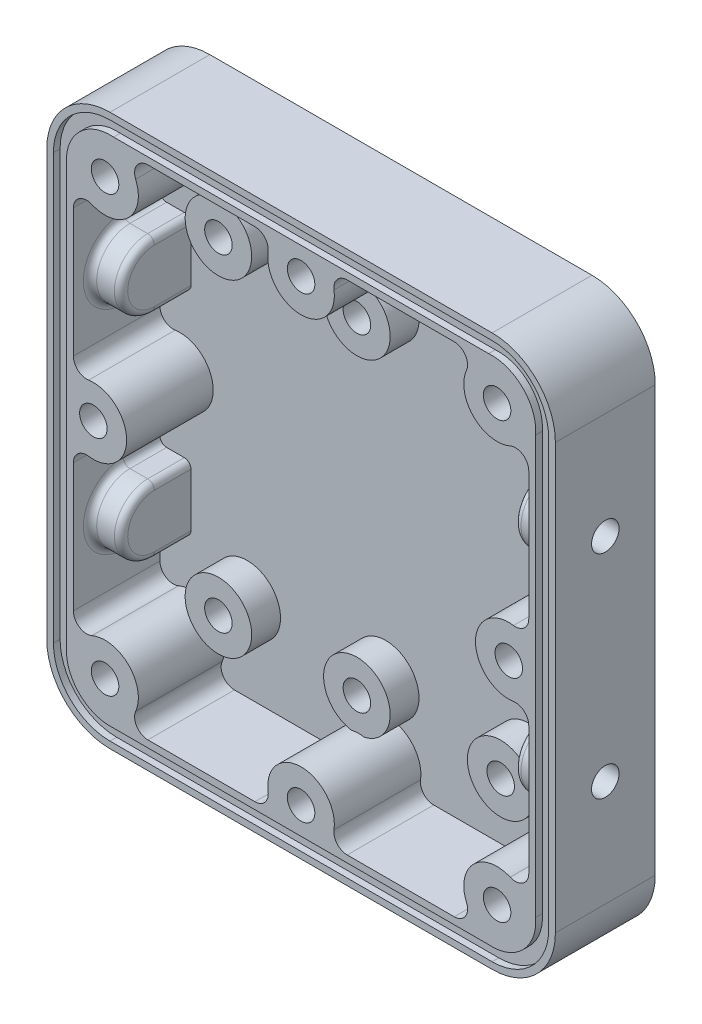
SolidWorks part; units mm, degrees
material "ABS"
ref_plane "X-Y Datum" through (0, 0, 0) normal (0, 0, 1) x (1, 0, 0)
ref_plane "X-Z Datum" through (0, 0, 0) normal (0, 1, 0) x (1, 0, 0)
ref_plane "Y-Z Datum" through (0, 0, 0) normal (1, 0, 0) x (0, 0, -1)
sketch "Sketch2" plane through (0, 0, 0) normal (0, 0, 1) x (1, 0, 0)
  line L5 (20.066, 67.818) -> (84.074, 67.818) construction
  line L6 (20.066, 67.818) -> (20.066, 139.954) construction
  line L7 (20.066, 139.954) -> (84.074, 139.954) construction
  line L8 (84.074, 67.818) -> (84.074, 139.954) construction
  line L9 (20.066, 67.818) -> (84.074, 139.954) construction
  line L10 (20.066, 139.954) -> (84.074, 67.818) construction
  line L14 (6.096, 153.924) -> (98.044, 153.924) construction
  line L15 (98.044, 53.848) -> (98.044, 153.924) construction
  line L16 (6.096, 53.848) -> (98.044, 53.848) construction
  line L17 (6.096, 53.848) -> (6.096, 153.924) construction
  line L18 (15.621, 153.924) -> (88.519, 153.924)
  line L19 (98.044, 63.373) -> (98.044, 144.399)
  line L20 (15.621, 53.848) -> (88.519, 53.848)
  line L21 (6.096, 63.373) -> (6.096, 144.399)
  line L22 (20.066, 103.886) -> (12.446, 103.886) construction
  line L23 (52.07, 67.818) -> (52.07, 60.198) construction
  line L24 (84.074, 103.886) -> (91.694, 103.886) construction
  line L25 (52.07, 139.954) -> (52.07, 147.574) construction
  line L26 (20.066, 139.954) -> (14.6778, 145.3421) construction
  circle A0 centre (25.292, 135.128) radius 2.1 construction
  circle A1 centre (51.708, 135.128) radius 2.1 construction
  circle A2 centre (79.14, 135.128) radius 2.1 construction
  circle A3 centre (51.708, 72.644) radius 2.1 construction
  circle A4 centre (79.14, 72.644) radius 2.1 construction
  circle A5 centre (25.292, 72.644) radius 2.1 construction
  arc A10 (88.519, 153.924) -> (98.044, 144.399) centre (88.519, 144.399) cw
  arc A11 (98.044, 63.373) -> (88.519, 53.848) centre (88.519, 63.373) cw
  arc A12 (15.621, 53.848) -> (6.096, 63.373) centre (15.621, 63.373) cw
  arc A13 (15.621, 153.924) -> (6.096, 144.399) centre (15.621, 144.399) ccw
  circle A20 centre (12.446, 103.886) radius 6.35 construction
  circle A21 centre (52.07, 60.198) radius 6.35 construction
  circle A22 centre (91.694, 103.886) radius 6.35 construction
  circle A23 centre (52.07, 147.574) radius 6.35 construction
  circle A24 centre (14.6778, 145.3421) radius 6.35 construction
  circle A25 centre (89.4622, 145.3421) radius 6.35 construction
  circle A26 centre (89.4622, 62.4298) radius 6.35 construction
  circle A27 centre (14.6778, 62.4298) radius 6.35 construction
  point P18 (52.07, 103.886)
  point P32 (20.066, 139.954)
  dimension "D1" = 9.525
  dimension "D3" = 13.97
extrude "Boss-Extrude1" add sketch "Sketch2" along normal blind 16.51
shell "Shell1" thickness 2.54
sketch "Sketch4" plane through (0, 0, 16.51) normal (0, 0, 1) x (1, 0, 0)
  line L8 (88.519, 155.194) -> (15.621, 155.194)
  line L9 (99.314, 63.373) -> (99.314, 144.399)
  line L10 (15.621, 52.578) -> (88.519, 52.578)
  line L11 (4.826, 144.399) -> (4.826, 63.373)
  line L12 (88.519, 155.194) -> (15.621, 155.194)
  line L13 (99.314, 63.373) -> (99.314, 144.399)
  line L14 (15.621, 52.578) -> (88.519, 52.578)
  line L15 (4.826, 144.399) -> (4.826, 63.373)
  line L20 (88.519, 153.924) -> (15.621, 153.924)
  line L21 (98.044, 63.373) -> (98.044, 144.399)
  line L22 (15.621, 53.848) -> (88.519, 53.848)
  line L23 (6.096, 144.399) -> (6.096, 63.373)
  line L24 (88.519, 153.924) -> (15.621, 153.924)
  line L25 (98.044, 63.373) -> (98.044, 144.399)
  line L26 (15.621, 53.848) -> (88.519, 53.848)
  line L27 (6.096, 144.399) -> (6.096, 63.373)
  arc A8 (99.314, 144.399) -> (88.519, 155.194) centre (88.519, 144.399) ccw
  arc A9 (88.519, 52.578) -> (99.314, 63.373) centre (88.519, 63.373) ccw
  arc A10 (4.826, 63.373) -> (15.621, 52.578) centre (15.621, 63.373) ccw
  arc A11 (15.621, 155.194) -> (4.826, 144.399) centre (15.621, 144.399) ccw
  arc A12 (99.314, 144.399) -> (88.519, 155.194) centre (88.519, 144.399) ccw
  arc A13 (88.519, 52.578) -> (99.314, 63.373) centre (88.519, 63.373) ccw
  arc A14 (4.826, 63.373) -> (15.621, 52.578) centre (15.621, 63.373) ccw
  arc A15 (15.621, 155.194) -> (4.826, 144.399) centre (15.621, 144.399) ccw
  arc A20 (98.044, 144.399) -> (88.519, 153.924) centre (88.519, 144.399) ccw
  arc A21 (88.519, 53.848) -> (98.044, 63.373) centre (88.519, 63.373) ccw
  arc A22 (6.096, 63.373) -> (15.621, 53.848) centre (15.621, 63.373) ccw
  arc A23 (15.621, 153.924) -> (6.096, 144.399) centre (15.621, 144.399) ccw
  arc A24 (98.044, 144.399) -> (88.519, 153.924) centre (88.519, 144.399) ccw
  arc A25 (88.519, 53.848) -> (98.044, 63.373) centre (88.519, 63.373) ccw
  arc A26 (6.096, 63.373) -> (15.621, 53.848) centre (15.621, 63.373) ccw
  arc A27 (15.621, 153.924) -> (6.096, 144.399) centre (15.621, 144.399) ccw
  dimension "D1" = 1.27
  dimension "D2" = 0
extrude "Cut-Extrude1" cut sketch "Sketch4" against normal blind 1.27
sketch "Sketch5" plane through (0, 0, 0) normal (0, 0, 1) x (1, 0, 0)
  line L20 (7.3152, 144.399) -> (7.3152, 63.373)
  line L21 (15.621, 55.0672) -> (88.519, 55.0672)
  line L22 (96.8248, 63.373) -> (96.8248, 144.399)
  line L23 (88.519, 152.7048) -> (15.621, 152.7048)
  line L24 (7.3152, 144.399) -> (7.3152, 63.373)
  line L25 (15.621, 55.0672) -> (88.519, 55.0672)
  line L26 (96.8248, 63.373) -> (96.8248, 144.399)
  line L27 (88.519, 152.7048) -> (15.621, 152.7048)
  line L48 (98.044, 63.373) -> (98.044, 144.399)
  line L49 (15.621, 53.848) -> (88.519, 53.848)
  line L50 (6.096, 144.399) -> (6.096, 63.373)
  line L51 (88.519, 153.924) -> (15.621, 153.924)
  line L52 (98.044, 63.373) -> (98.044, 144.399)
  line L53 (15.621, 53.848) -> (88.519, 53.848)
  line L54 (6.096, 144.399) -> (6.096, 63.373)
  line L55 (88.519, 153.924) -> (15.621, 153.924)
  arc A32 (7.3152, 63.373) -> (15.621, 55.0672) centre (15.621, 63.373) ccw
  arc A33 (88.519, 55.0672) -> (96.8248, 63.373) centre (88.519, 63.373) ccw
  arc A34 (96.8248, 144.399) -> (88.519, 152.7048) centre (88.519, 144.399) ccw
  arc A35 (15.621, 152.7048) -> (7.3152, 144.399) centre (15.621, 144.399) ccw
  arc A36 (7.3152, 63.373) -> (15.621, 55.0672) centre (15.621, 63.373) ccw
  arc A37 (88.519, 55.0672) -> (96.8248, 63.373) centre (88.519, 63.373) ccw
  arc A38 (96.8248, 144.399) -> (88.519, 152.7048) centre (88.519, 144.399) ccw
  arc A39 (15.621, 152.7048) -> (7.3152, 144.399) centre (15.621, 144.399) ccw
  arc A56 (98.044, 144.399) -> (88.519, 153.924) centre (88.519, 144.399) ccw
  arc A57 (88.519, 53.848) -> (98.044, 63.373) centre (88.519, 63.373) ccw
  arc A58 (6.096, 63.373) -> (15.621, 53.848) centre (15.621, 63.373) ccw
  arc A59 (15.621, 153.924) -> (6.096, 144.399) centre (15.621, 144.399) ccw
  arc A60 (98.044, 144.399) -> (88.519, 153.924) centre (88.519, 144.399) ccw
  arc A61 (88.519, 53.848) -> (98.044, 63.373) centre (88.519, 63.373) ccw
  arc A62 (6.096, 63.373) -> (15.621, 53.848) centre (15.621, 63.373) ccw
  arc A63 (15.621, 153.924) -> (6.096, 144.399) centre (15.621, 144.399) ccw
  dimension "D1" = 2.4892
  dimension "D2" = 0
extrude "Boss-Extrude2" add sketch "Sketch5" along normal up to surface (15.24 mm away) up to face at (52.07, 103.886, 15.24)
sketch "Sketch7" plane through (0, 0, 0) normal (0, 0, 1) x (1, 0, 0)
  line L1 (19.168, 149.8323) -> (16.2955, 152.7048)
  line L3 (10.1877, 140.852) -> (7.3152, 143.7245)
  line L4 (7.3152, 144.399) -> (7.3152, 63.373) construction
  line L5 (88.519, 152.7048) -> (15.621, 152.7048) construction
  line L6 (52.07, 103.886) -> (52.07, 122.8885) construction
  line L7 (1144.018, 103.886) -> (98.044, 103.886) construction
  line L8 (93.9523, 140.852) -> (96.8248, 143.7245)
  line L9 (84.972, 149.8323) -> (87.8445, 152.7048)
  line L10 (84.972, 57.9397) -> (87.8445, 55.0672)
  line L11 (93.9523, 66.92) -> (96.8248, 64.0475)
  line L12 (10.1877, 66.92) -> (7.3152, 64.0475)
  line L13 (19.168, 57.9397) -> (16.2955, 55.0672)
  line L14 (48.3287, 152.7048) -> (55.8113, 152.7048)
  line L15 (96.8248, 107.6273) -> (96.8248, 100.1447)
  line L17 (96.8248, 103.886) -> (7.3152, 103.886) construction
  line L18 (48.3287, 55.0672) -> (55.8113, 55.0672)
  line L20 (7.3152, 107.6273) -> (7.3152, 100.1447)
  line L21 (6.096, 103.886) -> (-1029.3668, 103.886) construction
  arc A0 (10.1877, 140.852) -> (19.168, 149.8323) centre (14.6778, 145.3421) ccw
  arc A1 (48.3287, 152.7048) -> (55.8113, 152.7048) centre (52.07, 147.574) ccw
  arc A3 (96.8248, 107.6273) -> (96.8248, 100.1447) centre (91.694, 103.886) ccw
  arc A5 (55.8113, 55.0672) -> (48.3287, 55.0672) centre (52.07, 60.198) ccw
  arc A7 (7.3152, 100.1447) -> (7.3152, 107.6273) centre (12.446, 103.886) ccw
  arc A8 (7.3152, 143.7245) -> (16.2955, 152.7048) centre (15.6763, 144.3437) cw
  arc A9 (96.8248, 143.7245) -> (87.8445, 152.7048) centre (88.4637, 144.3437) ccw
  arc A10 (93.9523, 140.852) -> (84.972, 149.8323) centre (89.4622, 145.3421) cw
  arc A11 (93.9523, 66.92) -> (84.972, 57.9397) centre (89.4622, 62.4298) ccw
  arc A12 (96.8248, 64.0475) -> (87.8445, 55.0672) centre (88.4637, 63.4283) cw
  arc A13 (7.3152, 64.0475) -> (16.2955, 55.0672) centre (15.6763, 63.4283) ccw
  arc A14 (10.1877, 66.92) -> (19.168, 57.9397) centre (14.6778, 62.4298) cw
extrude "Boss-Extrude3" add sketch "Sketch7" along normal up to surface (16.51 mm away)
sketch "Sketch8" plane through (0, 0, 0) normal (0, 0, 1) x (1, 0, 0)
  line L73 (95.504, 63.373) -> (95.504, 144.399)
  line L74 (15.621, 56.388) -> (88.519, 56.388)
  line L75 (8.636, 144.399) -> (8.636, 63.373)
  line L76 (88.519, 151.384) -> (15.621, 151.384)
  line L77 (95.504, 63.373) -> (95.504, 144.399)
  line L78 (15.621, 56.388) -> (88.519, 56.388)
  line L79 (8.636, 144.399) -> (8.636, 63.373)
  line L80 (88.519, 151.384) -> (15.621, 151.384)
  line L101 (96.8248, 63.373) -> (96.8248, 144.399)
  line L102 (15.621, 55.0672) -> (88.519, 55.0672)
  line L103 (7.3152, 144.399) -> (7.3152, 63.373)
  line L104 (88.519, 152.7048) -> (15.621, 152.7048)
  line L105 (96.8248, 63.373) -> (96.8248, 144.399)
  line L106 (15.621, 55.0672) -> (88.519, 55.0672)
  line L107 (7.3152, 144.399) -> (7.3152, 63.373)
  line L108 (88.519, 152.7048) -> (15.621, 152.7048)
  arc A37 (95.504, 144.399) -> (88.519, 151.384) centre (88.519, 144.399) ccw
  arc A38 (88.519, 56.388) -> (95.504, 63.373) centre (88.519, 63.373) ccw
  arc A39 (8.636, 63.373) -> (15.621, 56.388) centre (15.621, 63.373) ccw
  arc A40 (15.621, 151.384) -> (8.636, 144.399) centre (15.621, 144.399) ccw
  arc A41 (95.504, 144.399) -> (88.519, 151.384) centre (88.519, 144.399) ccw
  arc A42 (88.519, 56.388) -> (95.504, 63.373) centre (88.519, 63.373) ccw
  arc A43 (8.636, 63.373) -> (15.621, 56.388) centre (15.621, 63.373) ccw
  arc A44 (15.621, 151.384) -> (8.636, 144.399) centre (15.621, 144.399) ccw
  arc A61 (96.8248, 144.399) -> (88.519, 152.7048) centre (88.519, 144.399) ccw
  arc A62 (88.519, 55.0672) -> (96.8248, 63.373) centre (88.519, 63.373) ccw
  arc A63 (7.3152, 63.373) -> (15.621, 55.0672) centre (15.621, 63.373) ccw
  arc A64 (15.621, 152.7048) -> (7.3152, 144.399) centre (15.621, 144.399) ccw
  arc A65 (96.8248, 144.399) -> (88.519, 152.7048) centre (88.519, 144.399) ccw
  arc A66 (88.519, 55.0672) -> (96.8248, 63.373) centre (88.519, 63.373) ccw
  arc A67 (7.3152, 63.373) -> (15.621, 55.0672) centre (15.621, 63.373) ccw
  arc A68 (15.621, 152.7048) -> (7.3152, 144.399) centre (15.621, 144.399) ccw
  dimension "D1" = 2.54
  dimension "D2" = 1.2192
extrude "Boss-Extrude4" add sketch "Sketch8" along normal up to surface (16.51 mm away) up to face at (13.8498, 146.1702, 16.51)
sketch "Sketch9" plane through (0, 0, 16.51) normal (0, 0, 1) x (1, 0, 0)
  circle A0 centre (14.6778, 145.3421) radius 2.625
  circle A1 centre (52.07, 147.574) radius 2.625
  circle A2 centre (89.4622, 145.3421) radius 2.625
  circle A3 centre (91.694, 103.886) radius 2.6229
  circle A4 centre (12.446, 103.886) radius 2.625
  circle A5 centre (14.6778, 62.4298) radius 2.625
  circle A6 centre (52.07, 60.198) radius 2.625
  circle A7 centre (89.4622, 62.4298) radius 2.625
extrude "Cut-Extrude2" cut sketch "Sketch9" against normal blind 10
fillet "Fillet1" radius 2.54 16 edges at (8.636, 98.806, 8.255) (8.636, 108.966, 8.255) (8.636, 65.3683, 8.255) (17.6163, 56.388, 8.255) (57.15, 56.388, 8.255) (46.99, 56.388, 8.255) (86.5237, 56.388, 8.255) (95.504, 65.3683, 8.255) (95.504, 108.966, 8.255) (95.504, 98.806, 8.255) (95.504, 142.4037, 8.255) (86.5237, 151.384, 8.255) (46.99, 151.384, 8.255) (57.15, 151.384, 8.255) (17.6163, 151.384, 8.255) (8.636, 142.4037, 8.255)
sketch "Sketch10" plane through (0, 0, 0) normal (0, 0, 1) x (1, 0, 0)
  circle A0 centre (25.292, 135.128) radius 6.35
  circle A1 centre (51.708, 135.128) radius 6.35
  circle A2 centre (79.14, 135.128) radius 6.35
  circle A3 centre (79.14, 72.644) radius 6.35
  circle A4 centre (51.708, 72.644) radius 6.35
  circle A5 centre (25.292, 72.644) radius 6.35
  circle A6 centre (25.292, 135.128) radius 2.625
  circle A7 centre (51.708, 135.128) radius 2.625
  circle A8 centre (79.14, 135.128) radius 2.625
  circle A9 centre (79.14, 72.644) radius 2.625
  circle A10 centre (51.708, 72.644) radius 2.625
  circle A11 centre (25.292, 72.644) radius 2.625
extrude "Boss-Extrude5" add sketch "Sketch10" along normal blind 5.5
sketch "Sketch11" plane through (0, 0, 16.51) normal (0, 0, 1) x (1, 0, 0)
  line L6 (88.519, 156.464) -> (15.621, 156.464)
  line L7 (88.519, 156.464) -> (15.621, 156.464)
  line L19 (100.584, 63.373) -> (100.584, 144.399)
  line L20 (15.621, 51.308) -> (88.519, 51.308)
  line L21 (3.556, 144.399) -> (3.556, 63.373)
  line L22 (100.584, 63.373) -> (100.584, 144.399)
  line L23 (15.621, 51.308) -> (88.519, 51.308)
  line L24 (3.556, 144.399) -> (3.556, 63.373)
  circle A0 centre (14.6778, 145.3421) radius 2.1
  circle A1 centre (52.07, 147.574) radius 2.1
  circle A2 centre (89.4622, 145.3421) radius 2.1
  circle A3 centre (91.694, 103.886) radius 2.1
  circle A4 centre (89.4622, 62.4298) radius 2.1
  circle A5 centre (52.07, 60.198) radius 2.1
  circle A6 centre (14.6778, 62.4298) radius 2.1
  circle A7 centre (12.446, 103.886) radius 2.1
  arc A22 (100.584, 144.399) -> (88.519, 156.464) centre (88.519, 144.399) ccw
  arc A23 (88.519, 51.308) -> (100.584, 63.373) centre (88.519, 63.373) ccw
  arc A24 (3.556, 63.373) -> (15.621, 51.308) centre (15.621, 63.373) ccw
  arc A25 (15.621, 156.464) -> (3.556, 144.399) centre (15.621, 144.399) ccw
  arc A26 (88.519, 51.308) -> (100.584, 63.373) centre (88.519, 63.373) ccw
  arc A27 (3.556, 63.373) -> (15.621, 51.308) centre (15.621, 63.373) ccw
  arc A28 (15.621, 156.464) -> (3.556, 144.399) centre (15.621, 144.399) ccw
  arc A29 (100.584, 144.399) -> (88.519, 156.464) centre (88.519, 144.399) ccw
  point P24 (52.07, 103.886)
  dimension "D1" = 0
  dimension "D2" = 0
  dimension "D3" = 0
sketch "Sketch12" plane through (3.556, 0, 0) normal (-1, 0, 0) x (0, 0, 1)
  line L0 (6.985, 144.399) -> (6.985, 103.886) construction
  line L3 (16.51, 144.399) -> (-2.54, 144.399) construction
  line L4 (6.985, 103.886) -> (6.985, 63.373) construction
  line L5 (16.51, 63.373) -> (-2.54, 63.373) construction
  line L6 (6.985, 130.4925) -> (-2.54, 130.4925)
  line L7 (-2.54, 144.399) -> (-2.54, 63.373) construction
  line L8 (6.985, 117.7925) -> (-2.54, 117.7925)
  line L9 (6.985, 89.9795) -> (-2.54, 89.9795)
  line L10 (6.985, 77.2795) -> (-2.54, 77.2795)
  line L11 (-2.54, 77.2795) -> (-2.54, 89.9795)
  line L12 (-2.54, 130.4925) -> (-2.54, 117.7925)
  arc A0 (6.985, 117.7925) -> (6.985, 130.4925) centre (6.985, 124.1425) ccw
  arc A1 (6.985, 77.2795) -> (6.985, 89.9795) centre (6.985, 83.6295) ccw
  point P6 (6.985, 103.886)
extrude "Boss-Extrude6" add sketch "Sketch12" against normal blind 11
sketch "Sketch13" plane through (3.556, 0, 0) normal (-1, 0, 0) x (0, 0, 1)
  line L0 (6.985, 144.399) -> (6.985, 103.886) construction
  line L1 (6.985, 103.886) -> (6.985, 63.373) construction
  circle A0 centre (6.985, 124.1425) radius 2.625
  circle A1 centre (6.985, 83.6295) radius 2.625
extrude "Cut-Extrude3" cut sketch "Sketch13" against normal blind 8
ref_plane "Plane1" through (52.07, 0, 0) normal (1, 0, 0) x (0, 0, -1)
mirror "Mirror1" about plane through (52.07, 0, 0) normal (1, 0, 0) of "Cut-Extrude3", "Boss-Extrude6"
fillet "Fillet2" radius 1.27 24 edges at (89.584, 77.2795, 3.4925) (89.584, 89.9795, 3.4925) (95.504, 89.9795, 3.4925) (95.504, 77.2795, 3.4925) (8.636, 130.4925, 3.4925) (8.636, 117.7925, 3.4925) (8.636, 89.9795, 3.4925) (8.636, 77.2795, 3.4925) (89.584, 130.4925, 3.4925) (89.584, 124.1425, 13.335) (95.504, 130.4925, 3.4925) (95.504, 124.1425, 13.335) (14.556, 89.9795, 3.4925) (14.556, 83.6295, 13.335) (14.556, 130.4925, 3.4925) (14.556, 124.1425, 13.335) (89.584, 83.6295, 13.335) (95.504, 83.6295, 13.335) (8.636, 124.1425, 13.335) (8.636, 83.6295, 13.335) (89.584, 117.7925, 3.4925) (95.504, 117.7925, 3.4925) (14.556, 77.2795, 3.4925) (14.556, 117.7925, 3.4925)
